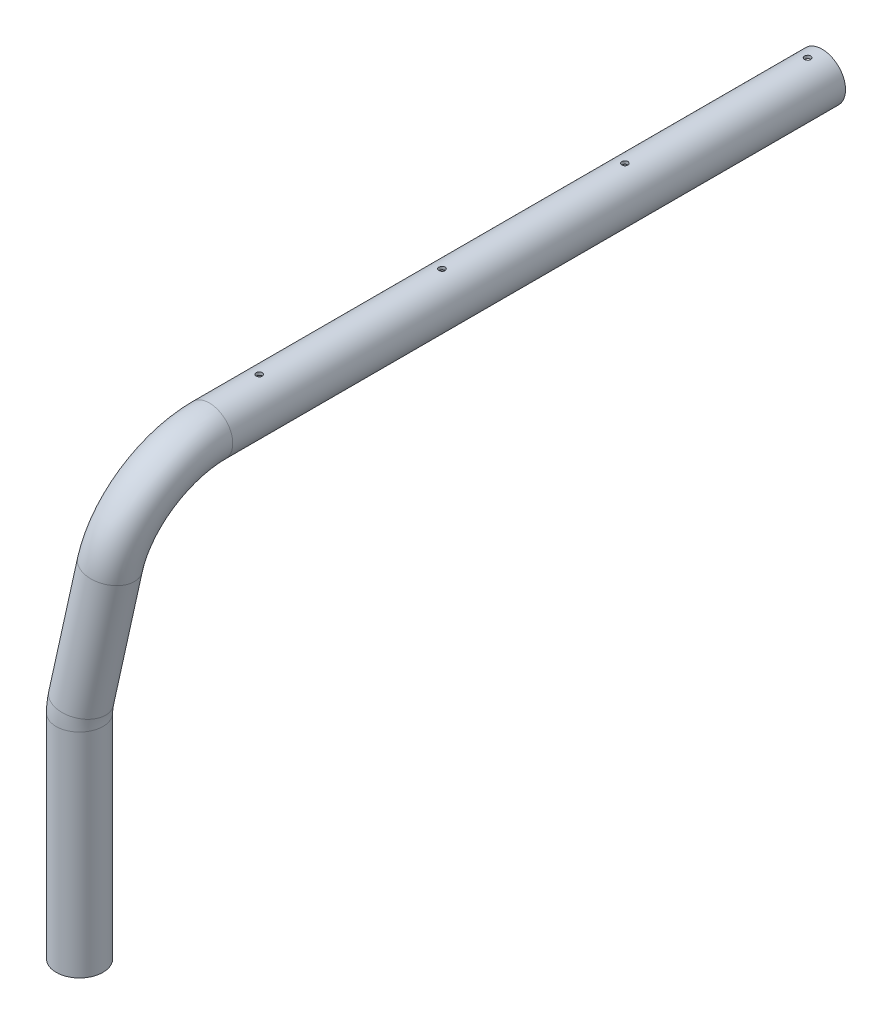
SolidWorks part; units mm, degrees
material "Aço carbono simples"
ref_plane "Plano frontal" through (0, 0, 0) normal (0, 0, 1) x (1, 0, 0)
ref_plane "Plano superior" through (0, 0, 0) normal (0, 1, 0) x (1, 0, 0)
ref_plane "Plano direito" through (0, 0, 0) normal (1, 0, 0) x (0, 0, -1)
sketch3d "3DSketch1"
  line L0 (0, 0, 0) -> (0, 145.6256, 0)
  line L1 (0.657, 154.308, -0.3813) -> (13.1262, 236.0687, -7.6171)
  line L2 (21.3837, 290.2133, -67.3888) -> (21.3837, 290.2133, -486.4089)
  arc A0 (13.1262, 236.0687, -7.6171) -> (21.3837, 290.2133, -67.3888) centre (12.3378, 230.8991, -67.3888) ccw
  arc A1 (0, 145.6256, 0) -> (0.657, 154.308, -0.3813) centre (43.246, 145.6256, -25.0955) ccw
  point P7 (21.3837, 290.2133, -12.4089)
  point P8 (-46.9764, 239.945, -67.3888)
  point P11 (0, 150, 0)
  point P12 (18.1505, 145.6256, -68.3415)
  dimension "D6" = 60
  dimension "D7" = 50
  dimension "D1" = 170
  dimension "D2" = 150
  dimension "D3" = 291
  dimension "D4" = 95
  dimension "D5" = 474
ref_plane "Plano1" through (0, 0, 0) normal (0, 1, 0) x (1, 0, 0)
sketch "Esboço1" plane through (0, 0, 0) normal (0, 1, 0) x (1, 0, 0)
  circle A0 centre (0, 0) radius 16
  circle A1 centre (0, 0) radius 14
  dimension "D1" = 32
  dimension "D2" = 2
sweep "Varredura1" add profiles "Esboço1" path "3DSketch1"
ref_plane "Plano2" through (0, 308, 0) normal (0, 1, 0) x (1, 0, 0)
hole_wizard "Furo roscado de M51" positions "Esboço2" profile "Esboço3" tap size "M5" standard "DIN"
sketch "Esboço2" plane through (0, 308, 0) normal (0, 1, 0) x (1, 0, 0)
  line L0 (37.3837, 486.4089) -> (5.3837, 486.4089) construction
  line L1 (5.3837, 486.4089) -> (5.3837, 67.3888) construction
  point P0 (21.3837, 476.4089)
  dimension "D1" = 10
  dimension "D2" = 16
sketch "Esboço3" plane through (21.3837, 308, -476.4089) normal (1, 0, 0) x (0, 0, 1)
  line L0 (0, 0) -> (0, 33.7867)
  line L1 (0, 33.7867) -> (2.1, 33.7867)
  line L2 (2.1, 33.7867) -> (2.1, 0)
  line L5 (2.1, 0) -> (0, 0)
  line L11 (0, -6.35) -> (0, 107.95) construction
  dimension "Thru Tap Drill Dia." = 4.2
  dimension "Thru Tap Drill Depth" = 33.7867
cosmetic thread "Rosca de furo1" parameters "D2"=5
sketch "Esboço4" plane through (0, 308, 0) normal (0, 1, 0) x (1, 0, 0)
  line L0 (21.3837, 486.4089) -> (21.3837, 378.5833) construction
  line L1 (37.3837, 486.4089) -> (5.3837, 486.4089) construction
pattern_linear "Padrão linear1" count 4 spacing 125 along (0, 0, 1) of "Furo roscado de M51"
